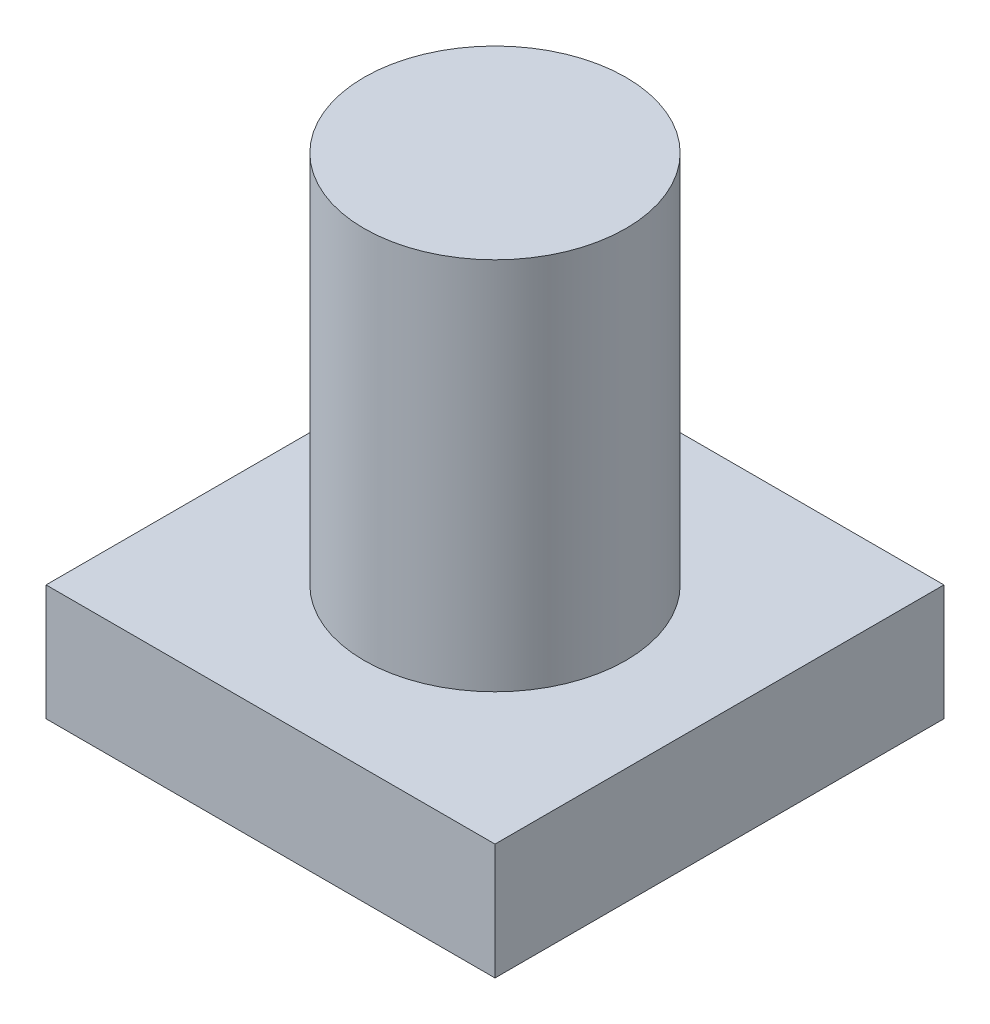
SolidWorks part; units mm, degrees
ref_plane "前视" through (0, 0, 0) normal (0, 0, 1) x (1, 0, 0)
ref_plane "上视" through (0, 0, 0) normal (0, 1, 0) x (1, 0, 0)
ref_plane "右视" through (0, 0, 0) normal (1, 0, 0) x (0, 0, -1)
sketch "草图1" plane through (0, 0, 0) normal (0, 1, 0) x (1, 0, 0)
  line L0 (0, 96.9306) -> (0, -101.3275) construction
  line L1 (-119.7143, 0) -> (134.9034, 0) construction
  line L3 (-6, 6) -> (6, 6)
  line L4 (-6, 6) -> (-6, -6)
  line L5 (-6, -6) -> (6, -6)
  line L6 (6, 6) -> (6, -6)
  dimension "D1" = 12
  dimension "D2" = 12
extrude "拉伸1" add sketch "草图1" along normal blind 3.1
sketch "草图2" plane through (0, 3.1, 0) normal (0, 1, 0) x (-1, 0, 0)
  line L0 (-6, 0) -> (8.7109, 0) construction
  line L1 (-6, 6) -> (-6, -6) construction
  line L2 (0, -7.8518) -> (0, 10.0992) construction
  circle A0 centre (0, 0) radius 3.5
  dimension "D1" = 7
extrude "拉伸2" add sketch "草图2" along normal blind 10
sketch "草图3" plane through (-6, 0, 0) normal (-1, 0, 0) x (0, 0, 1)
  line L0 (0, -6.9925) -> (0, 14.8526) construction
sketch "草图4" plane through (0, 13.1, 0) normal (0, 1, 0) x (-1, 0, 0)
  line L0 (0, -4.1469) -> (0, 4.9476) construction
  line L1 (-3.9082, 0) -> (5.1305, 0) construction
sketch "草图5" plane through (0, 0, 0) normal (0, -1, 0) x (1, 0, 0)
  line L0 (10.1949, 0) -> (-13.2034, 0) construction
  line L1 (0, 8.665) -> (0, -9.2576) construction
